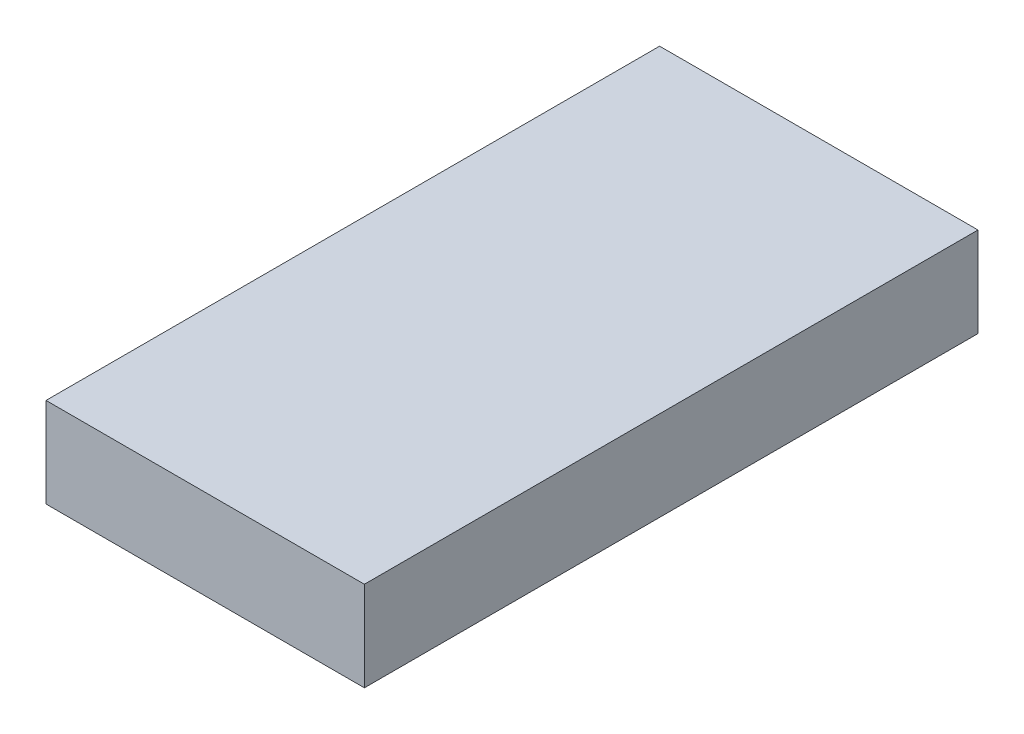
SolidWorks part; units mm, degrees
ref_plane "Front Plane" through (0, 0, 0) normal (0, 0, 1) x (1, 0, 0)
ref_plane "Top Plane" through (0, 0, 0) normal (0, 1, 0) x (1, 0, 0)
ref_plane "Right Plane" through (0, 0, 0) normal (1, 0, 0) x (0, 0, -1)
sketch "Sketch1" plane through (0, 0, 0) normal (0, 1, 0) x (1, 0, 0)
  line L1 (-21.8984, 41.933) -> (22.1016, 41.933)
  line L2 (-21.8984, 41.933) -> (-21.8984, -42.8649)
  line L3 (-21.8984, -42.8649) -> (22.1016, -42.8649)
  line L4 (22.1016, 41.933) -> (22.1016, -42.8649)
  dimension "D1" = 84.7979
  dimension "D2" = 43.9999
extrude "Boss-Extrude1" add sketch "Sketch1" along normal blind 12.4
sketch "Sketch2" plane through (-21.8984, 0, 0) normal (-1, 0, 0) x (0, 0, 1)
  line L0 (42.8649, 6.2) -> (-41.933, 6.2) construction
  line L1 (42.8649, 12.4) -> (42.8649, 0) construction
  line L2 (-41.933, 12.4) -> (-41.933, 0) construction
  text T0 "<b>Controller         </b>                  "
extrude "Cut-Extrude1" cut sketch "Sketch2" against normal blind 0.254
